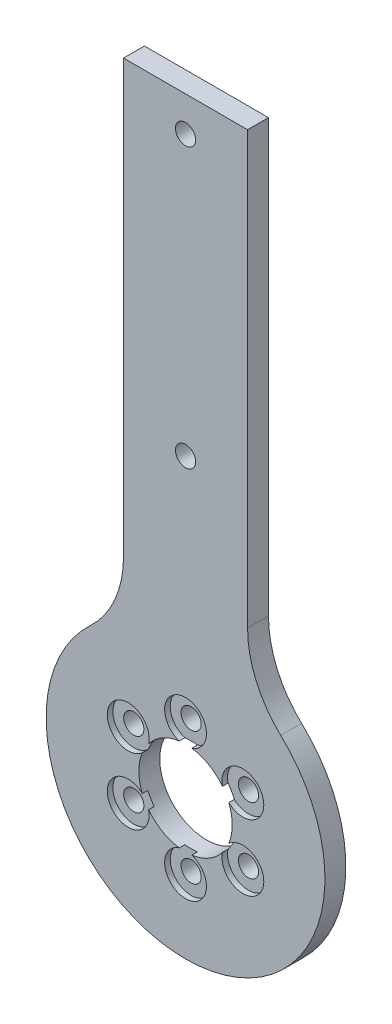
SolidWorks part; units mm, degrees
material "Thornel Mat VMA"
ref_plane "前视基准面" through (0, 0, 0) normal (0, 0, 1) x (1, 0, 0)
ref_plane "上视基准面" through (0, 0, 0) normal (0, 1, 0) x (1, 0, 0)
ref_plane "右视基准面" through (0, 0, 0) normal (1, 0, 0) x (0, 0, -1)
sketch "草图1" plane through (0, 0, 0) normal (0, 0, 1) x (1, 0, 0)
  circle A0 centre (0, 0) radius 20
  circle A1 centre (0, 0) radius 9.5 construction
  circle A2 centre (0, 0) radius 6.7
  circle A3 centre (0, 9.5) radius 1.45
  circle A4 centre (8.2272, 4.75) radius 1.45
  circle A5 centre (8.2272, -4.75) radius 1.45
  circle A6 centre (0, -9.5) radius 1.45
  circle A7 centre (-8.2272, -4.75) radius 1.45
  circle A8 centre (-8.2272, 4.75) radius 1.45
  point P19 (0, 0)
  dimension "D1" = 19
  dimension "D2" = 13.4
  dimension "D3" = 2.9
  dimension "D5" = 40
  dimension "D4" = 6
extrude "凸台-拉伸1" add sketch "草图1" along normal blind 3
sketch "草图2" plane through (0, 0, 0) normal (0, 0, 1) x (1, 0, 0)
  line L0 (0, 12.5) -> (0, 87.5) construction
  line L1 (-8.9, 12.5) -> (8.9, 12.5)
  line L2 (-8.9, 12.5) -> (-8.9, 87.5)
  line L3 (-8.9, 87.5) -> (8.9, 87.5)
  line L4 (8.9, 12.5) -> (8.9, 87.5)
  line L5 (-8.9, 12.5) -> (8.9, 87.5) construction
  line L6 (-8.9, 87.5) -> (8.9, 12.5) construction
  circle A0 centre (0, 9.5) radius 1.45 construction
  circle A1 centre (0, 42.5) radius 1.45
  circle A2 centre (0, 82.5) radius 1.45
  point P0 (0, 50)
  dimension "D4" = 2.9
  dimension "D1" = 3
  dimension "D2" = 17.8
  dimension "D3" = 75
  dimension "D5" = 40
  dimension "D6" = 5
extrude "凸台-拉伸2" add sketch "草图2" along normal blind 3
fillet "圆角1" radius 15 2 edges at (-8.9, 17.9106, 1.5) (8.9, 17.9106, 1.5)
sketch "草图3" plane through (0, 0, 3) normal (0, 0, 1) x (1, 0, 0)
  circle A0 centre (0, 9.5) radius 3
  circle A1 centre (8.2272, 4.75) radius 3
  circle A2 centre (8.2272, -4.75) radius 3
  circle A3 centre (0, -9.5) radius 3
  circle A4 centre (-8.2272, -4.75) radius 3
  circle A5 centre (-8.2272, 4.75) radius 3
  point P3 (1.5318, 0.4408)
  point P15 (0, 0)
  dimension "D1" = 6
  dimension "D2" = 6
extrude "切除-拉伸1" cut sketch "草图3" against normal blind 0.8
